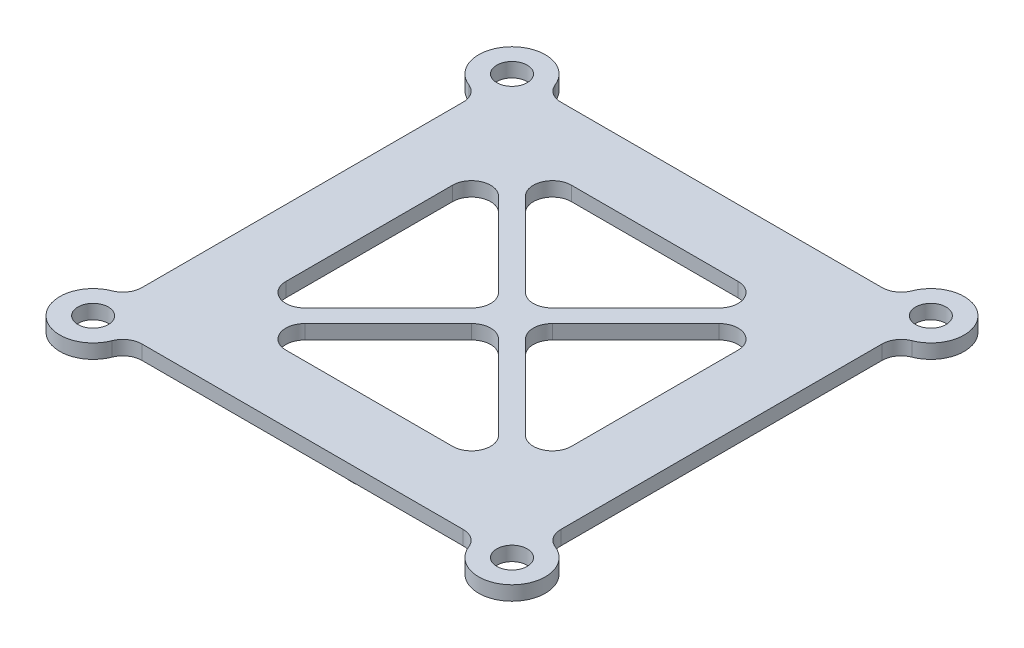
SolidWorks part; units mm, degrees
material "Thornel Mat VMA"
ref_plane "Front Plane" through (0, 0, 0) normal (0, 0, 1) x (1, 0, 0)
ref_plane "Top Plane" through (0, 0, 0) normal (0, 1, 0) x (1, 0, 0)
ref_plane "Right Plane" through (0, 0, 0) normal (1, 0, 0) x (0, 0, -1)
sketch "Sketch1" plane through (0, 0, 0) normal (0, 1, 0) x (1, 0, 0)
  line L1 (-18.5, -22) -> (18.5, -22)
  line L2 (-22, -18.5) -> (-22, 18.5)
  line L3 (-18.5, 22) -> (18.5, 22)
  line L4 (22, -18.5) -> (22, 18.5)
  line L5 (-22, -22) -> (22, 22) construction
  line L6 (-22, 22) -> (22, -22) construction
  arc A0 (-18.5, 22) -> (-22, 18.5) centre (-22, 22) ccw
  arc A1 (-22, -18.5) -> (-18.5, -22) centre (-22, -22) ccw
  arc A2 (18.5, -22) -> (22, -18.5) centre (22, -22) ccw
  arc A3 (22, 18.5) -> (18.5, 22) centre (22, 22) ccw
  point P0 (0, 0)
  dimension "D2" = 7
  dimension "D1" = 44
extrude "Boss-Extrude1" add sketch "Sketch1" along normal mid plane 1.5
fillet "Fillet1" radius 2 8 edges at (22, 0, 18.5) (18.5, 0, 22) (22, 0, -18.5) (18.5, 0, -22) (-18.5, 0, -22) (-22, 0, -18.5) (-22, 0, 18.5) (-18.5, 0, 22)
hole_wizard "Ø3.2 (3.2) Diameter Hole1" positions "Sketch3" profile "Sketch2" hole size "Ø3.2" standard "ANSI Metric"
sketch "Sketch3" plane through (0, 0.75, 0) normal (0, 1, 0) x (1, 0, 0)
  point P0 (-22, 22)
  point P3 (-22, -22)
  point P6 (22, -22)
  point P9 (22, 22)
sketch "Sketch2" plane through (-22, 0.75, -22) normal (1, 0, 0) x (0, 0, 1)
  line L0 (0, 0) -> (0, 10.9614)
  line L1 (0, 10.9614) -> (1.6, 10)
  line L2 (1.6, 10) -> (1.6, 0)
  line L5 (1.6, 0) -> (0, 0)
  line L10 (0, 10.9614) -> (-1.6, 10) construction
  line L11 (0, -6.35) -> (0, 107.95) construction
  dimension "Hole Dia." = 3.2
  dimension "Hole Depth" = 10
  dimension "Drill Angle" = 118
sketch "Sketch4" plane through (0, 0.75, 0) normal (0, 1, 0) x (1, 0, 0)
  line L2 (-15, 16.8765) -> (-15, -16.8765)
  line L3 (-15, 15) -> (-15, -15)
  line L5 (16.8765, 15) -> (-16.8765, 15)
  line L6 (15, 15) -> (-15, 15)
  line L8 (15, -16.8765) -> (15, 16.8765)
  line L9 (15, -15) -> (15, 15)
  line L10 (-15, 15) -> (15, -15)
  line L11 (-16.8765, -15) -> (16.8765, -15)
  line L12 (-15, -15) -> (15, -15)
  line L13 (15, 15) -> (-15, -15)
  line L14 (-14.2929, 15.7071) -> (15.7071, -14.2929)
  line L15 (-15.7071, 14.2929) -> (14.2929, -15.7071)
  line L16 (14.2929, 15.7071) -> (-15.7071, -14.2929)
  line L17 (15.7071, 14.2929) -> (-14.2929, -15.7071)
  dimension "D1" = 7
  dimension "D2" = 7
  dimension "D3" = 7
  dimension "D4" = 7
  dimension "D5" = 1
  dimension "D6" = 1
  dimension "D7" = 1
  dimension "D8" = 1
extrude "Cut-Extrude1" cut sketch "Sketch4" against normal blind 1.5 contours L16 L15 L3 | L16 L6 L14 | L9 L17 L14 | L15 L17 L12
fillet "Fillet2" radius 2 12 edges at (15, 0, 13.5858) (13.5858, 0, 15) (1.4142, 0, 0) (15, 0, -13.5858) (13.5858, 0, -15) (-13.5858, 0, -15) (0, 0, -1.4142) (-1.4142, 0, 0) (0, 0, 1.4142) (-13.5858, 0, 15) (-15, 0, 13.5858) (-15, 0, -13.5858)
sketch "Sketch5" plane through (0, -0.75, 0) normal (0, -1, 0) x (1, 0, 0)
  line L0 (-14.5802, -20.8746) -> (14.6513, -20.8746) construction
  text T0 "<b>AKASHDIP </b>" font "Century Gothic" height in points 16
  point P3 (0, 0)
  point P4 (-14.5802, -20.8746)
extrude "Boss-Extrude2" add sketch "Sketch5" along normal blind 0.7
sketch "Sketch6" plane through (0, -0.75, 0) normal (0, -1, 0) x (1, 0, 0)
  line L0 (-14.0389, 20.1896) -> (16.0926, 20.1896) construction
  text T0 "<b>May 2025</b>" font "Century Gothic" height in points 16
  point P3 (16.0926, 20.5312)
  point P4 (-14.0389, 20.5269)
extrude "Boss-Extrude3" add sketch "Sketch6" along normal blind 0.7
